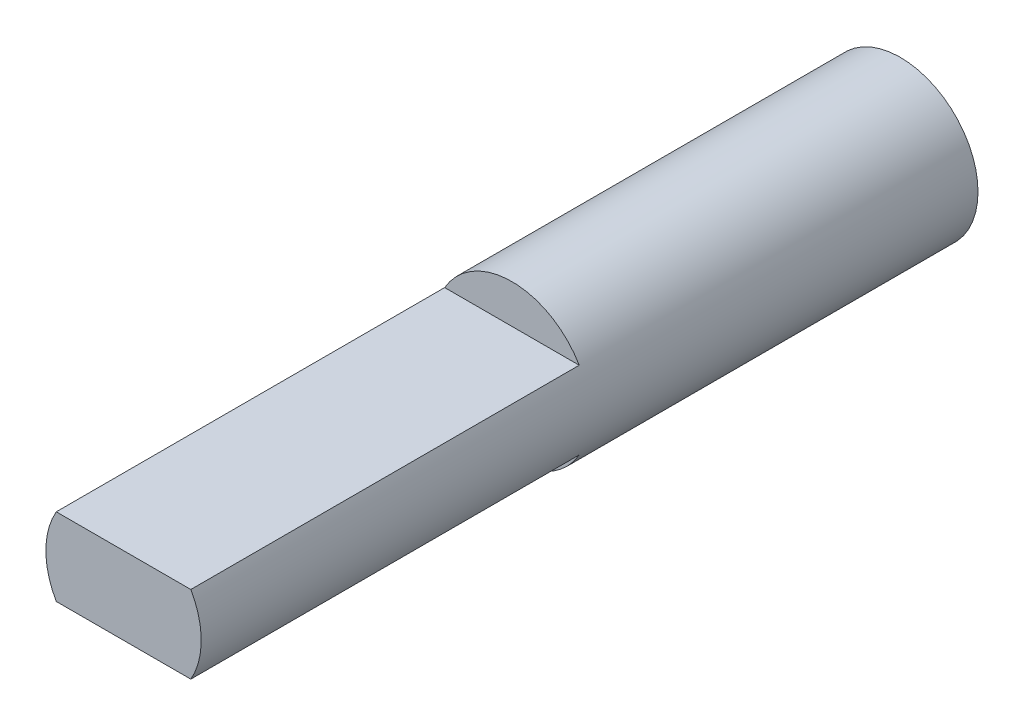
SolidWorks part; units mm, degrees
ref_plane "前视基准面" through (0, 0, 0) normal (0, 0, 1) x (1, 0, 0)
ref_plane "上视基准面" through (0, 0, 0) normal (0, 1, 0) x (1, 0, 0)
ref_plane "右视基准面" through (0, 0, 0) normal (1, 0, 0) x (0, 0, -1)
sketch "草图1" plane through (0, 0, 0) normal (0, 0, 1) x (1, 0, 0)
  circle A0 centre (-12.6379, 12.301) radius 1
extrude "凸台-拉伸1" add sketch "草图1" along normal blind 5
sketch "草图2" plane through (0, 0, 5) normal (0, 0, 1) x (1, 0, 0)
  line L0 (-13.5039, 12.801) -> (-11.7718, 12.801)
  line L1 (-13.5039, 11.801) -> (-11.7718, 11.801)
  line L2 (-13.6379, 12.301) -> (-11.6379, 12.301) construction
  arc A0 (-13.5039, 12.801) -> (-13.5039, 11.801) centre (-12.6379, 12.301) ccw
  arc A3 (-11.7718, 12.801) -> (-11.7718, 11.801) centre (-12.6379, 12.301) cw
  dimension "D2" = 1
extrude "凸台-拉伸2" add sketch "草图2" along normal blind 5
